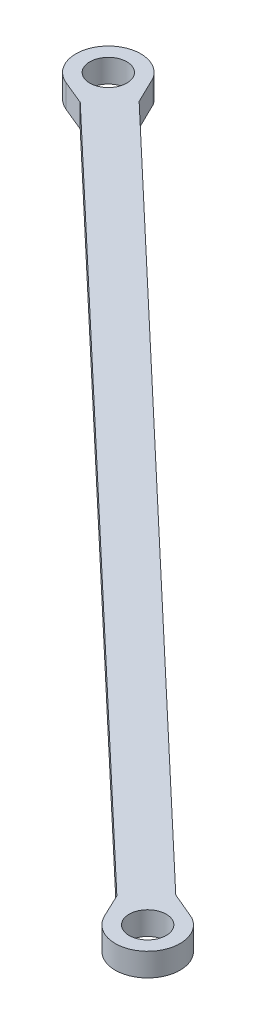
SolidWorks part; units mm, degrees
material "Thornel Mat VMA"
ref_plane "前视基准面" through (0, 0, 0) normal (0, 0, 1) x (1, 0, 0)
ref_plane "上视基准面" through (0, 0, 0) normal (0, 1, 0) x (1, 0, 0)
ref_plane "右视基准面" through (0, 0, 0) normal (1, 0, 0) x (0, 0, -1)
sketch "草图1" plane through (0, 0, 0) normal (0, 1, 0) x (1, 0, 0)
  line L0 (-82.3901, 53.8373) -> (70.0058, -90.6463)
  line L1 (-82.3901, 53.8373) -> (-76.1979, 60.3686)
  line L2 (-6.1922, -18.4045) -> (0, -11.8732)
  line L3 (-76.1979, 60.3686) -> (76.1979, -84.115)
  line L4 (73.1018, -87.3806) -> (-79.294, 57.103) construction
  line L5 (-79.0798, 66.2784) -> (-76.1979, 60.3686)
  line L6 (-87.6195, 55.9944) -> (-82.3901, 53.8373)
  line L7 (72.4383, -95.7534) -> (70.0058, -90.6463)
  line L8 (82.2528, -86.678) -> (76.1979, -84.115)
  line L9 (70.0058, -90.6463) -> (76.1979, -84.115)
  circle A3 centre (-84.9502, 62.4655) radius 4
  circle A4 centre (-84.9502, 62.4655) radius 7
  circle A5 centre (78.7581, -92.7432) radius 7
  circle A6 centre (78.7581, -92.7432) radius 4
  dimension "D1" = 105
  dimension "D2" = 9
extrude "凸台-拉伸1" add sketch "草图1" along normal blind 5 contours L4 A4 L5 A3 | L4 L1 L5 A4 | L1 L4 A4 L6 | A4 L4 A3 | L4 L2 L3 L1 | L2 L4 L1 L0 | L9 L4 L2 L0 | L4 L9 L3 L2 | A5 L4 L9 L7 | A5 L4 A6 | L4 A5 L8 L9 | L4 A5 L8 A6
